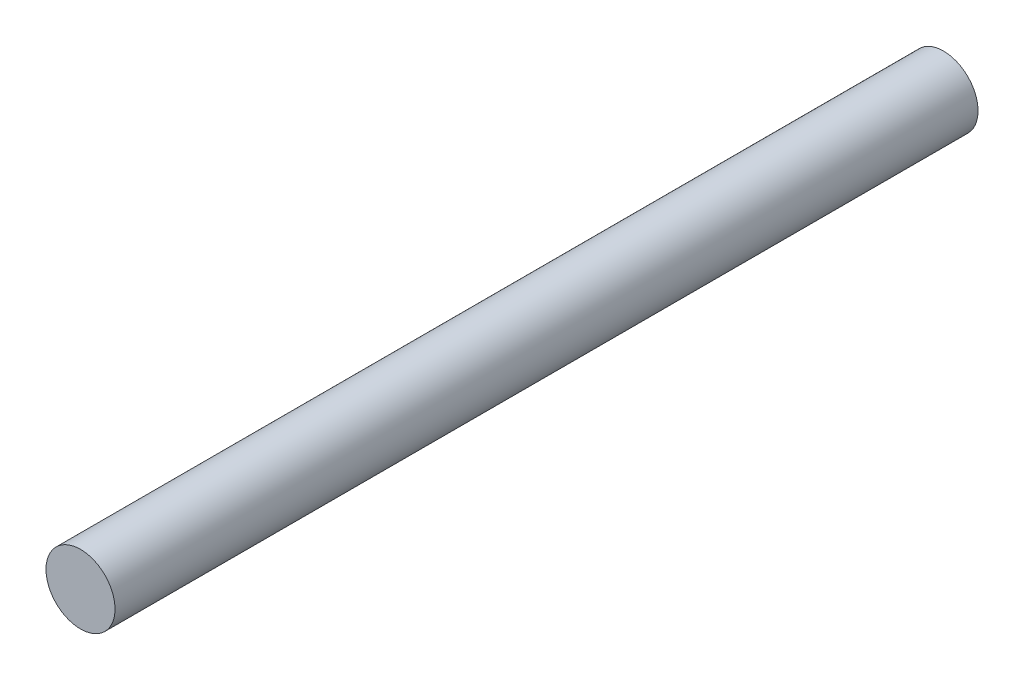
SolidWorks part; units mm, degrees
ref_plane "前视基准面" through (0, 0, 0) normal (0, 0, 1) x (1, 0, 0)
ref_plane "上视基准面" through (0, 0, 0) normal (0, 1, 0) x (1, 0, 0)
ref_plane "右视基准面" through (0, 0, 0) normal (1, 0, 0) x (0, 0, -1)
ref_plane "基准面1" through (0, 0, 0) normal (0, -1, 0) x (1, 0, 0)
sketch "草图1" plane through (0, 0, 0) normal (0, -1, 0) x (1, 0, 0)
  line L0 (4, 50) -> (0, 50)
  line L1 (0, 50) -> (0, -50)
  line L2 (0, -50) -> (4, -50)
  line L3 (4, -50) -> (4, 50)
  line L4 (0, 50) -> (0, -50) construction
  line L5 (0, 65.9846) -> (0, -76.9341) construction
  dimension "D1" = 100
  dimension "D2" = 8
revolve "旋转1" add sketch "草图1" angle 360 about L4
